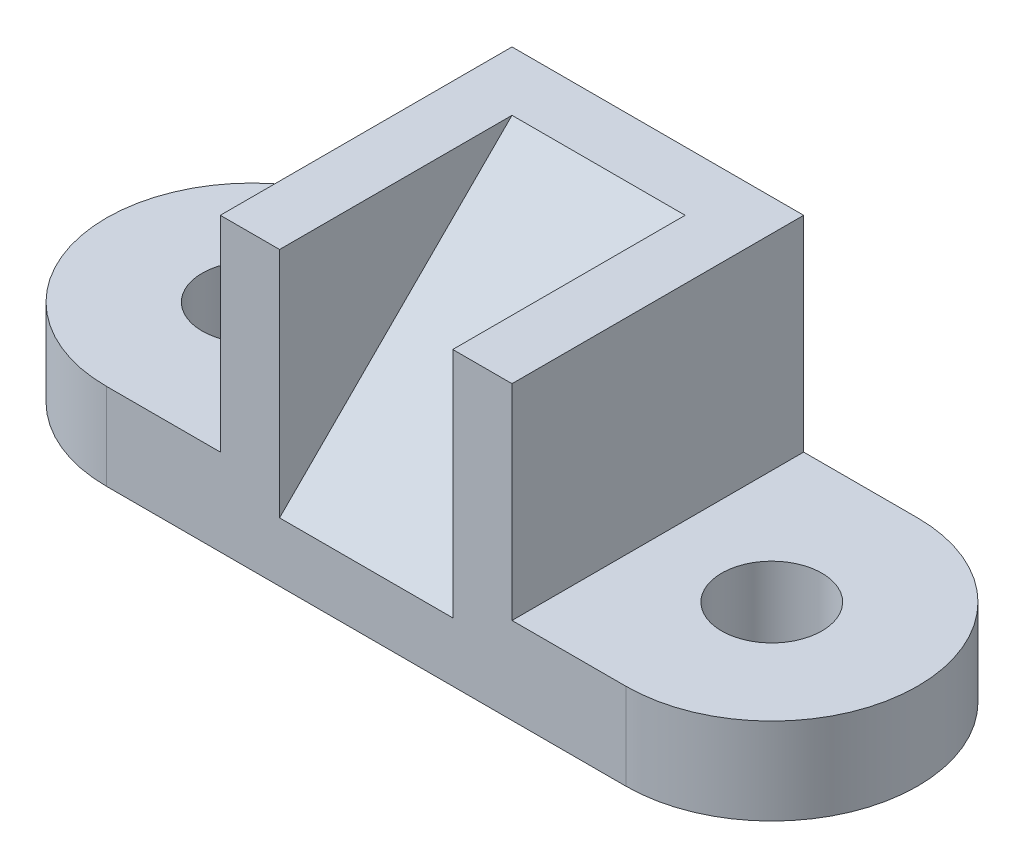
SolidWorks part; units mm, degrees
ref_plane "Front Plane" through (0, 0, 0) normal (0, 0, 1) x (1, 0, 0)
ref_plane "Top Plane" through (0, 0, 0) normal (0, 1, 0) x (1, 0, 0)
ref_plane "Right Plane" through (0, 0, 0) normal (1, 0, 0) x (0, 0, -1)
sketch "Sketch1" plane through (0, 0, 0) normal (0, 1, 0) x (1, 0, 0)
  line L0 (0, 0) -> (114, 0) construction
  line L1 (0, -32) -> (114, -32)
  line L2 (0, 32) -> (114, 32)
  circle A0 centre (0, 0) radius 11
  circle A1 centre (114, 0) radius 11
  arc A2 (0, 32) -> (0, -32) centre (0, 0) ccw
  arc A3 (114, -32) -> (114, 32) centre (114, 0) ccw
  dimension "D1" = 22
  dimension "D2" = 22
  dimension "D3" = 64
  dimension "D4" = 64
  dimension "D5" = 114
  dimension "D6" = 114
  dimension "D7" = 114
extrude "Boss-Extrude1" add sketch "Sketch1" along normal blind 19
sketch "Sketch2" plane through (0, 19, 0) normal (0, 1, 0) x (1, 0, 0)
  line L0 (11, 0) -> (103, 0) construction
  line L1 (114, 32) -> (0, 32) construction
  line L2 (25, -32) -> (89, -32)
  line L3 (25, -32) -> (25, 32)
  line L4 (25, 32) -> (89, 32)
  line L5 (89, -32) -> (89, 32)
  line L6 (25, -32) -> (89, 32) construction
  line L7 (25, 32) -> (89, -32) construction
  circle A0 centre (0, 0) radius 11 construction
  circle A1 centre (114, 0) radius 11 construction
  point P7 (57, 0)
  dimension "D1" = 64
extrude "Boss-Extrude2" add sketch "Sketch2" along normal blind 45
ref_plane "Plane1" through (57, 0, 0) normal (-1, 0, 0) x (0, 0, 1)
sketch "Sketch3" plane through (57, 0, 0) normal (-1, 0, 0) x (0, 0, 1)
  line L0 (32, 64) -> (-19, 64)
  line L1 (-32, 64) -> (32, 64) construction
  line L2 (-19, 64) -> (32, 13)
  line L3 (32, 19) -> (32, 0) construction
  line L4 (32, 13) -> (32, 64)
  dimension "D1" = 51
  dimension "D2" = 51
extrude "Cut-Extrude1" cut sketch "Sketch3" against normal mid plane 38
